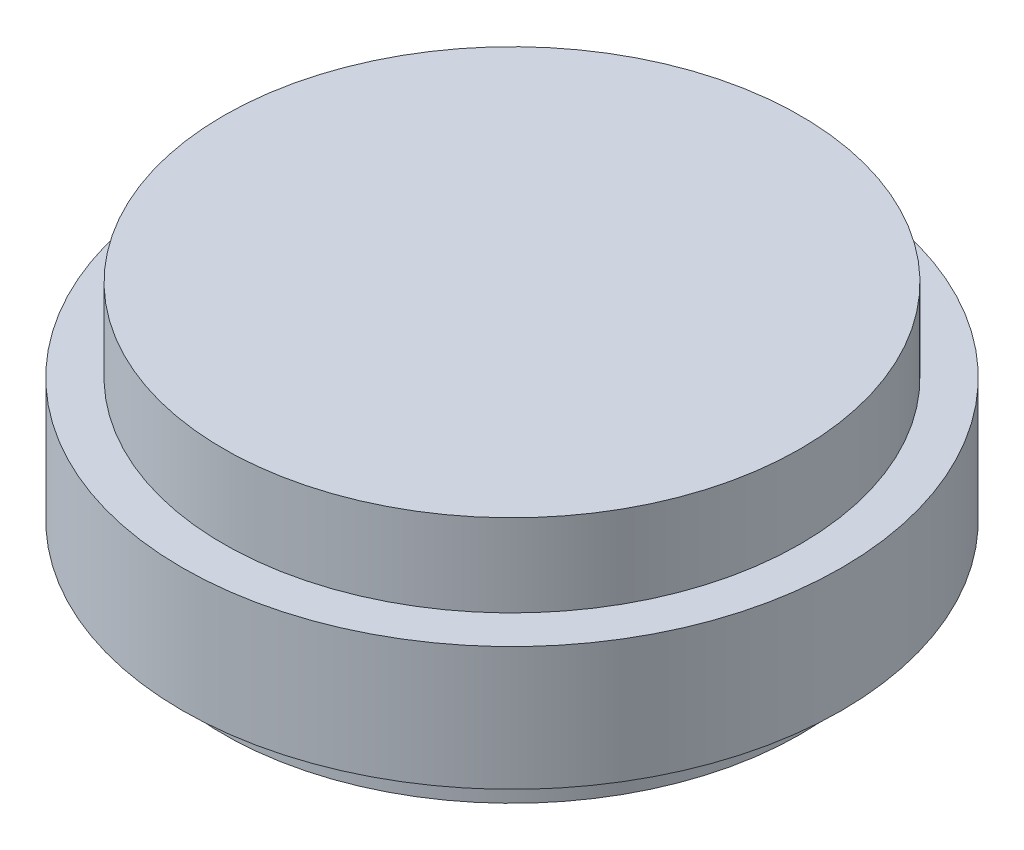
SolidWorks part; units mm, degrees
ref_plane "Plan de face" through (0, 0, 0) normal (0, 0, 1) x (1, 0, 0)
ref_plane "Plan de dessus" through (0, 0, 0) normal (0, 1, 0) x (1, 0, 0)
ref_plane "Plan de droite" through (0, 0, 0) normal (1, 0, 0) x (0, 0, -1)
sketch "Esquisse1" plane through (0, 0, 0) normal (0, 0, 1) x (1, 0, 0)
  line L0 (0, 0) -> (3.5, 0)
  line L1 (3.5, 0) -> (3.5, 0.5)
  line L2 (3.5, 0.5) -> (4, 0.5)
  line L3 (4, 0.5) -> (4, 2)
  line L4 (4, 2) -> (3.5, 2)
  line L5 (3.5, 2) -> (3.5, 3)
  line L6 (3.5, 3) -> (0, 3)
  line L7 (0, 3) -> (0, 0)
  dimension "D1" = 3.5
  dimension "D2" = 3.5
  dimension "D3" = 4
  dimension "D4" = 3
  dimension "D5" = 2
  dimension "D6" = 0.5
revolve "Révolution1" add sketch "Esquisse1" angle 360 about L7
